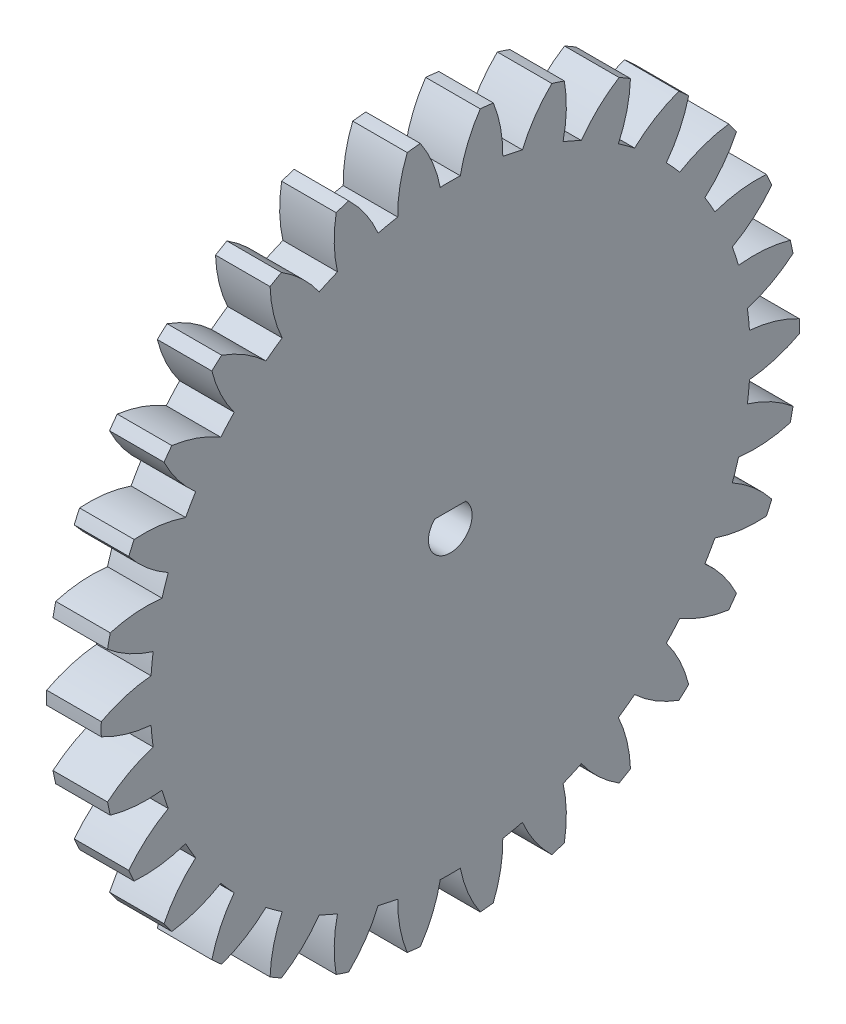
SolidWorks part; units mm, degrees
ref_plane "Plane1" through (0, 0, 0) normal (0, 0, 1) x (1, 0, 0)
ref_plane "Plane2" through (0, 0, 0) normal (0, 1, 0) x (1, 0, 0)
ref_plane "Plane3" through (0, 0, 0) normal (1, 0, 0) x (0, 0, -1)
sketch "HoldingSke" plane through (0, 0, 0) normal (0, 1, 0) x (1, 0, 0)
  line L0 (0, 0) -> (0.433, -0.25)
  line L1 (-15, 0) -> (100, 0) construction
  line L2 (0, 0) -> (-2.1039, 2.3779)
  line L3 (0, 0) -> (-11.863, 4.5341)
  line L4 (0, 0) -> (7.479, 4.318)
  line L5 (0, 0) -> (-46.8476, -17.4728)
  line L6 (0, 0) -> (-4.1448, -2.7965)
  line L7 (-2.1039, 2.3779) -> (8.6586, 51.2059)
  line L8 (-76.2, 54.61) -> (-75.5, 54.61)
  line L9 (-71.009, 38.7566) -> (-53.1078, 45.2721)
  line L10 (-76.2, 71.12) -> (104.1128, 71.12)
  line L11 (0, 0) -> (-5, 0)
  line L12 (-76.2, 101.6) -> (-76.133, 101.6)
  line L13 (24.9733, 27.94) -> (52.9518, 28.4284)
  line L14 (24.9733, 27.94) -> (24.9743, 27.94)
  line L15 (24.9733, 27.94) -> (100.4006, 29.5858)
  line L16 (-63.627, -2) -> (-12.827, -2)
  circle A0 centre (0, 0) radius 2
  circle A1 centre (0, 0) radius 27.499
  circle A2 centre (0, 0) radius 37.5
  circle A3 centre (0, 0) radius 2
  dimension "MHD" = 54.998
  dimension "Hub_dia" = 75
  dimension "Bore" = 4
  dimension "MBD" = 4
  dimension "Num_teeth" = 30
  dimension "Pitch" = 0.5
  dimension "Overall_len" = 50
  dimension "Show_teeth" = 30
  dimension "Thickness" = 5
  dimension "OAL" = 50.0001
  dimension "T_dim" = 0.7
  dimension "Ap" = 20
  dimension "H" = 19.05
  dimension "Pitch_radius" = 180.3128
  dimension "Width" = 5
  dimension "Backlash" = 0.067
  dimension "Addendum_fac" = 1
  dimension "Dedendum_fac" = 1.25
  dimension "Clearance_fac" = 0.25
  dimension "Dedendum_add" = 0.001
  dimension "Module" = 2
sketch "BasProSke" plane through (0, 0, 0) normal (0, 1, 0) x (1, 0, 0)
  line L0 (-10, 0) -> (60, 0) construction
  line L1 (0, 0) -> (0, 32)
  line L2 (0, 0) -> (5, 0)
  line L3 (5, 0) -> (5, 32)
  line L4 (5, 32) -> (0, 32)
  dimension "Thickness" = 5
  dimension "Diameter" = 64
revolve "Base-Revolve" add sketch "BasProSke" angle 360 about L0
sketch "TooCutSke" plane through (0, 0, 0) normal (1, 0, 0) x (0, 0, -1)
  line L1 (0, 0) -> (0, 107) construction
  line L2 (0, 0) -> (-1.6873, 29.9525) construction
  line L3 (0, 0) -> (-6.2643, 59.6013) construction
  line L4 (-1.6873, 29.9525) -> (-3.1322, 29.8007) construction
  arc A0 (0.9186, 27.4837) -> (-0.9186, 27.4837) centre (0, 0) ccw
  arc A1 (2.7618, 31.9061) -> (-2.7618, 31.9061) centre (0, 0) ccw
  circle A2 centre (0, 0) radius 30 construction
  circle A3 centre (0, 0) radius 28.1908 construction
  arc A4 (-0.9186, 27.4837) -> (-2.7618, 31.9061) centre (-12.6936, 25.1712) ccw
  arc A5 (2.7618, 31.9061) -> (0.9186, 27.4837) centre (12.6936, 25.1712) ccw
  dimension "Root_dia" = 54.998
  dimension "Overcut_dia" = 64.0508
  dimension "Pitch_dia" = 60
  dimension "Base_dia" = 56.3816
  dimension "Flank_rad" = 12
  dimension "Half_ang" = 6
  dimension "Half_CT" = 1.4528
extrude "ToothCut" cut sketch "TooCutSke" along normal through all
fillet "Breaks" [suppressed] radius 0.04
fillet "RootFillets" [suppressed] radius 0.501
pattern_circular "TeethCuts" count 30 every 12 about axis through (-10, 0, 0) along (1, 0, 0) of "ToothCut", "RootFillets", "Breaks"
sketch "HubNeaOneSke" plane through (0, 0, 0) normal (-1, 0, 0) x (0, 0, 1)
  circle A0 centre (0, 0) radius 27.499
  dimension "Diameter" = 54.998
extrude "HubNearOne" [suppressed] add sketch "HubNeaOneSke" along normal blind 45.0001
sketch "HubNeaBotSke" plane through (0, 0, 0) normal (-1, 0, 0) x (0, 0, 1)
  circle A0 centre (0, 0) radius 27.499
  dimension "Diameter" = 54.998
extrude "HubNearBoth" [suppressed] add sketch "HubNeaBotSke" along normal blind 22.5
ref_plane "FarPln" through (5, 0, 0) normal (1, 0, 0) x (0, 0, -1)
sketch "HubFarSke" plane through (5, 0, 0) normal (1, 0, 0) x (0, 0, -1)
  circle A0 centre (0, 0) radius 27.499
  dimension "Diameter" = 54.998
extrude "HubFar" [suppressed] add sketch "HubFarSke" along normal blind 22.5
sketch "BorSke" plane through (0, 0, 0) normal (1, 0, 0) x (0, 0, -1)
  circle A0 centre (0, 0) radius 2
  dimension "Diameter" = 4
extrude "Bore" cut sketch "BorSke" along normal mid plane 100.0001
sketch "KeySke" plane through (0, 0, 0) normal (1, 0, 0) x (0, 0, -1)
  line L0 (-0.8, 0) -> (-0.8, 2.7)
  line L1 (-0.8, 2.7) -> (0.8, 2.7)
  line L2 (0.8, 2.7) -> (0.8, 0)
  line L3 (0, 0) -> (0, 34) construction
  line L4 (-0.8, 0) -> (0.8, 0)
  dimension "Offset" = 2.7
  dimension "Width" = 1.6
extrude "Keyway" [suppressed] cut sketch "KeySke" along normal mid plane 100.0001
pattern_circular "Keyway2" [suppressed] count 2 every 90 about axis through (-10, 0, 0) along (1, 0, 0)
sketch "Sketch1" plane through (5, 0, 0) normal (1, 0, 0) x (0, 0, -1)
  line L0 (-1.4283, 1.4) -> (1.4283, 1.4)
  circle A0 centre (0, 0) radius 2 construction
  arc A1 (1.4283, 1.4) -> (-1.4283, 1.4) centre (0, 0) ccw
  dimension "D1" = 1.4
extrude "Boss-Extrude1" add sketch "Sketch1" against normal blind 5
equation "' \"Module@HoldingSke\" = 6.35"
equation "' \"Num_teeth@HoldingSke\" = 12"
equation "' \"Ap@HoldingSke\" =  20"
equation "' \"Ap@HoldingSke\" = 20"
equation "' \"Width@HoldingSke\" = 0.5 * 25.4"
equation "' \"Hub_dia@HoldingSke\"= 1 * 25.4"
equation "' \"Hub_dia@HoldingSke\" = 1 * 25.4"
equation "' \"Overall_len@HoldingSke\" = 1.0 * 25.4"
equation "' \"Bore@HoldingSke\" = 0.75 * 25.4"
equation "' \"T_dim@HoldingSke\" = 0.1 * 25.4"
equation "' \"Width@KeySke\" = 0.25 * 25.4"
equation "' \"Show_teeth@HoldingSke\" = 13"
equation "' \"Backlash@HoldingSke\" = 0.009 * 25.4"
equation "' \"Addendum_fac@HoldingSke\" = 1.0"
equation "' \"Dedendum_fac@HoldingSke\" = 1.25"
equation "' \"Dedendum_add@HoldingSke\" = 0.00005 * 25.4"
equation "' \"Clearance_fac@HoldingSke\" = 0.25"
equation "\"Pitch@HoldingSke\" = 1 / \"Module@HoldingSke\""
equation "\"Overcut_dia@TooCutSke\" = (\"Num_teeth@HoldingSke\" + 2 * \"Addendum_fac@HoldingSke\") / \"Pitch@HoldingSke\" + 0.002 * 25.4"
equation "\"Pitch_dia@TooCutSke\" = \"Num_teeth@HoldingSke\" / \"Pitch@HoldingSke\""
equation "\"Base_dia@TooCutSke\" = \"Num_teeth@HoldingSke\" / \"Pitch@HoldingSke\" * cos((\"Ap@HoldingSke\"  * 3.14159265 / 180))"
equation "\"Root_dia@TooCutSke\" = (\"Num_teeth@HoldingSke\" + 2) / \"Pitch@HoldingSke\" - 2 * (\"Addendum_fac@HoldingSke\" + \"Dedendum_fac@HoldingSke\") / \"Pitch@HoldingSke\" - \"Dedendum_add@HoldingSke\" * 2"
equation "\"Half_ang@TooCutSke\" = 180 / \"Num_teeth@HoldingSke\""
equation "\"Half_CT@TooCutSke\" = \"Num_teeth@HoldingSke\" / \"Pitch@HoldingSke\" * sin((3.14159265 / 2 / \"Num_teeth@HoldingSke\")) / 2 - 7 * \"Backlash@HoldingSke\" / 4"
equation "\"Flank_rad@TooCutSke\" = \"Num_teeth@HoldingSke\" / \"Pitch@HoldingSke\" / 5"
equation "\"Radius@RootFillets\" = \"Clearance_fac@HoldingSke\" / \"Pitch@HoldingSke\" + \"Dedendum_add@HoldingSke\""
equation "\"Break_rad@Breaks\" = 0.02 / \"Pitch@HoldingSke\""
equation "\"Thickness@HoldingSke\" = \"Width@HoldingSke\""
equation "\"OAL@HoldingSke\" = \"Thickness@HoldingSke\""
equation "\"MHD@HoldingSke\" = (\"Num_teeth@HoldingSke\" + 2) / \"Pitch@HoldingSke\" - 2 * (\"Addendum_fac@HoldingSke\" + \"Dedendum_fac@HoldingSke\")  / \"Pitch@HoldingSke\" - \"Dedendum_add@HoldingSke\" * 2"
equation "\"MBD@HoldingSke\" = (\"Num_teeth@HoldingSke\" + 2) / \"Pitch@HoldingSke\" - 2 * (\"Addendum_fac@HoldingSke\" + \"Dedendum_fac@HoldingSke\")  / \"Pitch@HoldingSke\" - \"Dedendum_add@HoldingSke\" * 2 - 0.002 * 25.4"
equation "\"MHD@HoldingSke\" = ((sgn( \"MHD@HoldingSke\" - \"Hub_dia@HoldingSke\" )-1)*( \"MHD@HoldingSke\" - \"Hub_dia@HoldingSke\" ))/-2+ \"Hub_dia@HoldingSke\""
equation "\"MBD@HoldingSke\" = ((sgn( \"MBD@HoldingSke\" - \"Bore@HoldingSke\" )-1)*( \"MBD@HoldingSke\" - \"Bore@HoldingSke\" ))/-2+ \"Bore@HoldingSke\""
equation "\"OAL@HoldingSke\" = ((sgn( \"OAL@HoldingSke\" - \"Overall_len@HoldingSke\" )+1)*( \"OAL@HoldingSke\" - \"Overall_len@HoldingSke\" ))/2 + \"Overall_len@HoldingSke\" + 0.000002 * 25.4"
equation "\"Num_teeth@TeethCuts\" = int( \"Show_teeth@HoldingSke\" ) + 1"
equation "\"Num_teeth@TeethCuts\" = ((sgn( \"Num_teeth@TeethCuts\" - \"Num_teeth@HoldingSke\" )-1)*( \"Num_teeth@TeethCuts\" - \"Num_teeth@HoldingSke\" ))/-2+ \"Num_teeth@HoldingSke\""
equation "\"Num_teeth@TeethCuts\" = ((sgn( \"Num_teeth@TeethCuts\" - 2.0)+1)*( \"Num_teeth@TeethCuts\" - 2.0))/2 +2.0"
equation "\"Angle@TeethCuts\" = 360.0 / \"Num_teeth@HoldingSke\""
equation "\"Diameter@BasProSke\" = (\"Num_teeth@HoldingSke\" + 2 * \"Addendum_fac@HoldingSke\") / \"Pitch@HoldingSke\""
equation "\"Thickness@BasProSke\"  = \"Thickness@HoldingSke\""
equation "' \"Fillet_rad@BasProSke\" =  \"Thickness@HoldingSke\" * 0.05"
equation "' \"Fillet_rad@BasProSke\" = \"Thickness@HoldingSke\" * 0.05"
equation "\"MHD@HoldingSke\" = ((sgn( \"MHD@HoldingSke\" - \"Root_dia@TooCutSke\" )-1)*( \"MHD@HoldingSke\" - \"Root_dia@TooCutSke\" ))/-2+ \"Root_dia@TooCutSke\""
equation "\"Diameter@HubNeaOneSke\" = \"MHD@HoldingSke\""
equation "\"Length@HubNearOne\" = \"OAL@HoldingSke\" - \"Thickness@BasProSke\""
equation "\"Diameter@HubNeaBotSke\" = \"MHD@HoldingSke\""
equation "\"Length@HubNearBoth\" = ( \"OAL@HoldingSke\" - \"Thickness@BasProSke\" ) / 2.0"
equation "\"Thickness@FarPln\" = \"Thickness@BasProSke\""
equation "\"Diameter@HubFarSke\" = \"MHD@HoldingSke\""
equation "\"Length@HubFar\" = ( \"OAL@HoldingSke\" - \"Thickness@BasProSke\" ) / 2.0"
equation "\"Diameter@BorSke\" = \"MBD@HoldingSke\""
equation "\"D1@Bore\" = \"OAL@HoldingSke\" * 2.0"
equation "\"D1@Keyway\" = \"OAL@HoldingSke\" * 2.0"
equation "\"Offset@KeySke\" = \"T_dim@HoldingSke\" + \"MBD@HoldingSke\" / 2.0"
